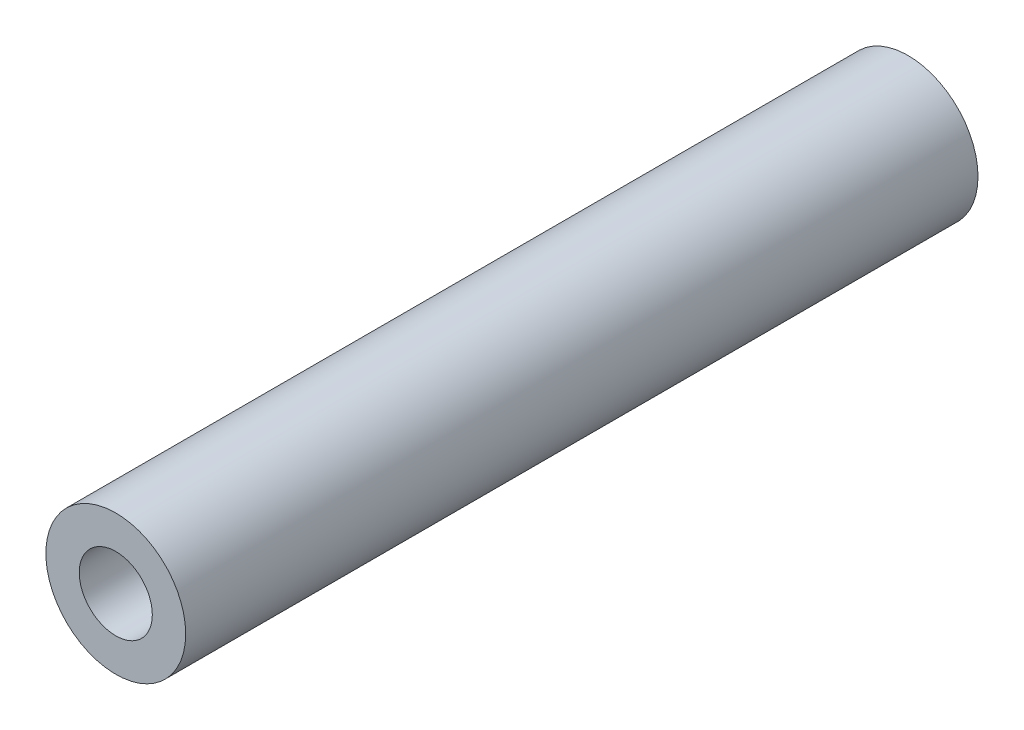
SolidWorks part; units mm, degrees
ref_plane "Front Plane" through (0, 0, 0) normal (0, 0, 1) x (1, 0, 0)
ref_plane "Top Plane" through (0, 0, 0) normal (0, 1, 0) x (1, 0, 0)
ref_plane "Right Plane" through (0, 0, 0) normal (1, 0, 0) x (0, 0, -1)
sketch "Sketch1" plane through (0, 0, 0) normal (0, 0, 1) x (1, 0, 0)
  circle A0 centre (0, 0) radius 2.4892
  circle A1 centre (0, 0) radius 4.7625
  dimension "D1" = 4.9784
  dimension "D2" = 9.525
extrude "Boss-Extrude1" add sketch "Sketch1" along normal mid plane 53.975
